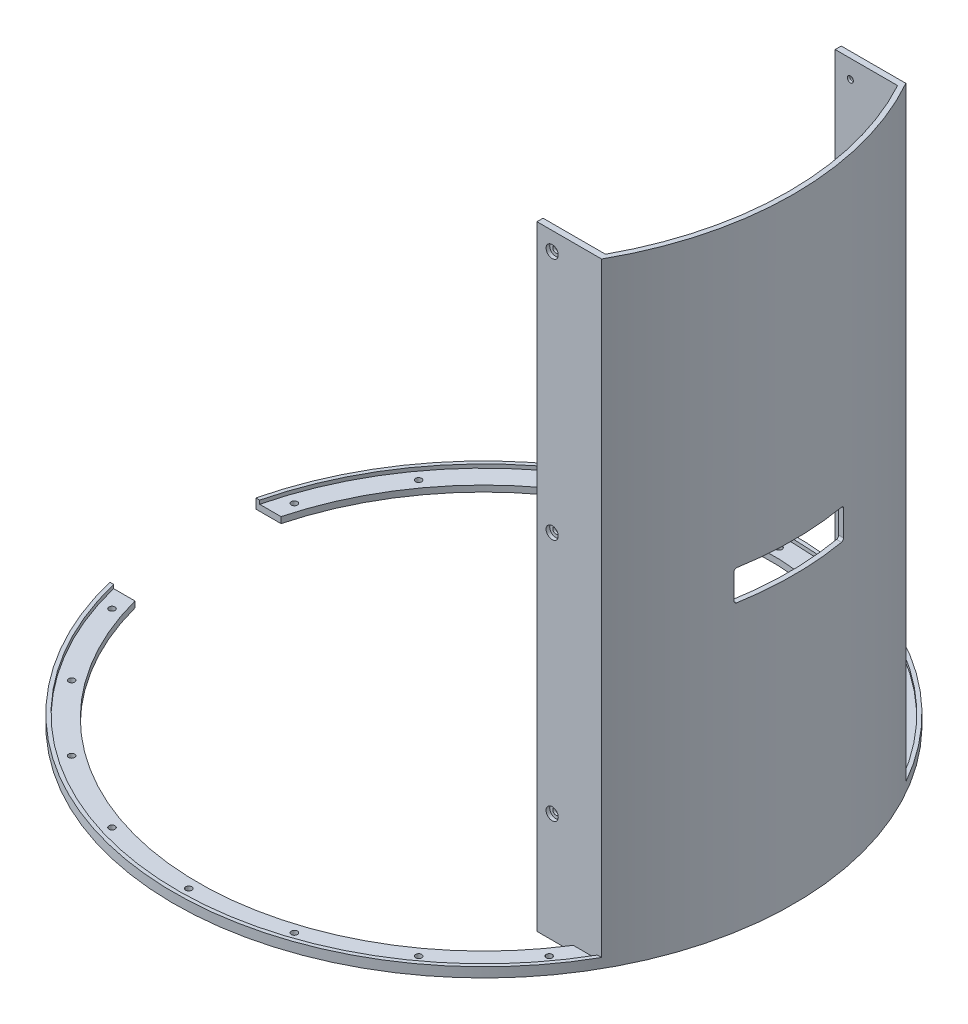
SolidWorks part; units mm, degrees
ref_plane "Front Plane" through (0, 0, 0) normal (0, 0, 1) x (1, 0, 0)
ref_plane "Top Plane" through (0, 0, 0) normal (0, 1, 0) x (1, 0, 0)
ref_plane "Right Plane" through (0, 0, 0) normal (1, 0, 0) x (0, 0, -1)
sketch "Sketch1" plane through (0, 0, 0) normal (0, 1, 0) x (1, 0, 0)
  circle A0 centre (0, 0) radius 254.5
  circle A1 centre (0, 0) radius 234.5
  dimension "D1" = 20
extrude "Boss-Extrude1" add sketch "Sketch1" along normal blind 5
sketch "Sketch2" plane through (0, 5, 0) normal (0, 1, 0) x (1, 0, 0)
  line L0 (254.5, 0) -> (234.5, 0)
  line L1 (221.6873, 125) -> (198.4068, 125)
  line L3 (168.5, 125) -> (165.5, 125) construction
  arc A0 (254.5, 0) -> (221.6873, 125) centre (0, 0) ccw
  circle A2 centre (0, 0) radius 254.5 construction
  circle A7 centre (0, 0) radius 234.5 construction
  arc A8 (198.4068, 125) -> (234.5, 0) centre (0, 0) cw
  dimension "D1" = 0
  dimension "D2" = 0
extrude "Boss-Extrude2" add sketch "Sketch2" along normal blind 500
mirror "Mirror1" about plane through (0, 505, 0) normal (0, 0, 1) of "Boss-Extrude2"
sketch "Sketch3" plane through (0, 5, 0) normal (0, 1, 0) x (1, 0, 0)
  line L1 (-254.5, 0) -> (-226.6942, 0)
  line L2 (-254.5, 0) -> (-254.5, 60)
  line L3 (-254.5, 60) -> (-226.6942, 60)
  line L4 (-226.6942, 0) -> (-226.6942, 60)
  arc A0 (221.6873, 125) -> (221.6873, -125) centre (0, 0) ccw construction
  arc A1 (198.4068, 125) -> (198.4068, -125) centre (0, 0) ccw construction
  dimension "D1" = 60
extrude "Cut-Extrude1" cut sketch "Sketch3" against normal blind 500
mirror "Mirror2" about plane through (0, 0, 0) normal (0, 0, 1) of "Cut-Extrude1"
sketch "Sketch4" plane through (0, 505, 0) normal (0, 1, 0) x (1, 0, 0)
  circle A0 centre (0, 0) radius 250.5
  arc A1 (221.6873, -125) -> (221.6873, 125) centre (0, 0) ccw construction
  dimension "D1" = 4
extrude "Cut-Extrude2" cut sketch "Sketch4" against normal blind 500
sketch "Sketch8" plane through (0, 5, 0) normal (0, 1, 0) x (1, 0, 0)
  line L0 (217.0835, 125) -> (168.5835, 125)
  line L1 (168.5835, 125) -> (168.5835, 120)
  line L2 (168.5835, 120) -> (220.0458, 120)
  line L3 (220.0458, 120) -> (220.0458, 125)
  line L4 (221.6873, 125) -> (217.0835, 125) construction
  line L5 (220.0458, 125) -> (217.0835, 125)
  dimension "D1" = 5
  dimension "D2" = 48.5
extrude "Boss-Extrude3" add sketch "Sketch8" along normal blind 500
mirror "Mirror3" about plane through (0, 0, 0) normal (0, 0, 1) of "Boss-Extrude3"
sketch "Sketch10" plane through (0, 0, 0) normal (0, -1, 0) x (1, 0, 0)
  line L0 (168.5835, 125) -> (168.5835, -125)
  line L1 (168.5835, 125) -> (208.5835, 125)
  line L2 (168.5835, -125) -> (208.5835, -125)
  arc A3 (208.5835, 125) -> (208.5835, -125) centre (0, 0) cw
  arc M3 (-226.6942, 60) -> (-226.6942, -60) centre (0, 0) cw
extrude "Boss-Extrude4" add sketch "Sketch10" against normal blind 5 contours L0 L2 L1 M3
sketch "Sketch11" plane through (0, 5, 0) normal (0, 1, 0) x (1, 0, 0)
  line L0 (168.5835, -120) -> (168.5835, 120) construction
  line L1 (168.5835, 93.5) -> (190, 93.5)
  line L2 (168.5835, 93.5) -> (168.5835, -96.5)
  line L3 (168.5835, -96.5) -> (190, -96.5)
  line L4 (190, 93.5) -> (190, -96.5)
  line L5 (188.5, -95) -> (188.5, -75) construction
  line L6 (168.5, -95) -> (188.5, -95) construction
  line L7 (188.5, 95) -> (168.5, 95) construction
  point P10 (178.5, -95)
  dimension "D1" = 1.5
  dimension "D2" = 1.5
  dimension "D3" = 1.5
extrude "Cut-Extrude3" cut sketch "Sketch11" against normal blind 10
sketch "Sketch12" plane through (0, 5, 0) normal (0, 1, 0) x (1, 0, 0)
  line L0 (-2.75, 0) -> (2.75, 0) construction
  line L1 (168.5835, 120) -> (185, 120)
  line L2 (168.5835, 120) -> (168.5835, 93.5)
  line L3 (168.5835, 93.5) -> (190, 93.5)
  line L4 (190, 115) -> (190, 93.5)
  line L5 (190, 93.5) -> (213, 93.5)
  line L6 (190, 93.5) -> (190, 75)
  line L7 (190, 75) -> (213, 75)
  line L8 (218, 88.5) -> (218, 80)
  line L9 (218, -88.5) -> (218, -80)
  line L10 (190, -75) -> (213, -75)
  line L11 (190, -93.5) -> (190, -75)
  line L12 (190, -93.5) -> (213, -93.5)
  line L13 (190, -115) -> (190, -93.5)
  line L14 (168.5835, -93.5) -> (190, -93.5)
  line L15 (168.5835, -120) -> (168.5835, -93.5)
  line L16 (168.5835, -120) -> (185, -120)
  arc A0 (213, -93.5) -> (218, -88.5) centre (213, -88.5) ccw
  arc A1 (218, -80) -> (213, -75) centre (213, -80) ccw
  arc A2 (190, -115) -> (185, -120) centre (185, -115) cw
  arc A3 (213, 75) -> (218, 80) centre (213, 80) ccw
  arc A4 (218, 88.5) -> (213, 93.5) centre (213, 88.5) ccw
  arc A5 (190, 115) -> (185, 120) centre (185, 115) ccw
  point P20 (218, -93.5)
  point P23 (218, -75)
  point P26 (190, -120)
  point P29 (218, 75)
  point P32 (218, 93.5)
  point P35 (190, 120)
  line M3 (190, 93.5) -> (190, -96.5)
  line M4 (190, -96.5) -> (168.5835, -96.5)
  line M5 (168.5835, -96.5) -> (168.5835, -120)
  line M6 (168.5835, -120) -> (219.8869, -120)
  dimension "D2" = 5
  dimension "D1" = 28
extrude "Cut-Extrude4" cut sketch "Sketch12" against normal blind 10 contours L8 L5 L7 M3 | L9 A1 L10 L12 A0 M3 | A2 L13 M4 M5 M6 | L4 A5 L1 L2 L3
fillet "Fillet1" radius 5 4 edges at (190, 2.5, 93.5) (190, 2.5, -93.5) (190, 2.5, -75) (190, 2.5, 75)
sketch "Sketch15" plane through (0, 5, 0) normal (0, 1, 0) x (1, 0, 0)
  circle A0 centre (242.5, 0) radius 2.5
  circle A1 centre (196.1866, -142.5379) radius 2.5
  circle A2 centre (74.9366, -230.6312) radius 2.5
  circle A3 centre (-74.9366, -230.6312) radius 2.5
  circle A4 centre (-196.1866, -142.5379) radius 2.5
  circle A5 centre (-242.5, 0) radius 2.5
  circle A6 centre (-196.1866, 142.5379) radius 2.5
  circle A7 centre (-74.9366, 230.6312) radius 2.5
  circle A8 centre (74.9366, 230.6312) radius 2.5
  circle A9 centre (196.1866, 142.5379) radius 2.5
  point P23 (0, 0)
  dimension "D1" = 242.5
  dimension "D2" = 10
extrude "Cut-Extrude5" cut sketch "Sketch15" against normal blind 10
sketch "Sketch16" plane through (0, 5, 0) normal (0, 1, 0) x (1, 0, 0)
  line L0 (-226.6942, 60) -> (-247.3262, 60) construction
  line L1 (221.6873, 125) -> (198.4068, 125) construction
  line L2 (-247.3262, 60) -> (-244.2381, 60)
  line L3 (221.6873, 125) -> (218.2367, 125)
  line L4 (-2.75, 0) -> (2.75, 0) construction
  line L5 (221.6873, -125) -> (218.2367, -125)
  line L6 (-247.3262, -60) -> (-244.2381, -60)
  arc A0 (221.6873, 125) -> (-247.3262, 60) centre (0, 0) ccw
  arc A1 (218.2367, 125) -> (-244.2381, 60) centre (0, 0) ccw
  arc A2 (218.2367, -125) -> (-244.2381, -60) centre (0, 0) cw
  arc A3 (221.6873, -125) -> (-247.3262, -60) centre (0, 0) cw
  dimension "D1" = 3
extrude "Boss-Extrude5" add sketch "Sketch16" along normal blind 3
sketch "Sketch18" plane through (0, 5, 0) normal (0, 1, 0) x (1, 0, 0)
  circle A0 centre (0, -242.5) radius 2.5
  circle A1 centre (-142.5379, -196.1866) radius 2.5
  circle A2 centre (-230.6312, -74.9366) radius 2.5
  circle A3 centre (-230.6312, 74.9366) radius 2.5
  circle A4 centre (-142.5379, 196.1866) radius 2.5
  circle A5 centre (0, 242.5) radius 2.5
  circle A6 centre (142.5379, 196.1866) radius 2.5
  circle A7 centre (230.6312, 74.9366) radius 2.5
  circle A8 centre (230.6312, -74.9366) radius 2.5
  circle A9 centre (142.5379, -196.1866) radius 2.5
  point P23 (0, 0)
  dimension "D1" = 242.5
  dimension "D2" = 10
extrude "Cut-Extrude6" cut sketch "Sketch18" against normal blind 5
sketch "Sketch19" plane through (0, 0, 0) normal (0, -1, 0) x (1, 0, 0)
  line L1 (193, 20) -> (207, 20)
  line L2 (190, 17) -> (190, -17)
  line L3 (193, -20) -> (207, -20)
  line L4 (210, 17) -> (210, -17)
  line L5 (193, -20) -> (190, -20)
  line L7 (190, -20) -> (190, -17)
  line L8 (193, 20) -> (190, 20)
  line L9 (190, 20) -> (190, 17)
  arc A1 (207, -20) -> (210, -17) centre (207, -17) ccw
  arc A2 (210, 17) -> (207, 20) centre (207, 17) ccw
  point P14 (190, 20)
extrude "Cut-Extrude7" cut sketch "Sketch19" against normal blind 7
fillet "Fillet2" radius 5 2 edges at (190, 2.5, 20) (190, 2.5, -20)
sketch "Sketch21" plane through (0, 5, 0) normal (0, 1, 0) x (1, 0, 0)
  line L0 (207, 20) -> (195, 20) construction
  line L1 (195, -20) -> (207, -20) construction
  line L2 (190, 25) -> (190, 70) construction
  line L3 (190, -70) -> (190, -25) construction
  circle A0 centre (200, 50) radius 2.5
  circle A1 centre (200, -50) radius 2.5
  dimension "D1" = 30
  dimension "D2" = 30
  dimension "D3" = 10
  dimension "D4" = 10
extrude "Cut-Extrude8" cut sketch "Sketch21" against normal blind 10
sketch "Sketch22" plane through (0, 0, 125) normal (0, 0, 1) x (1, 0, 0)
  line L0 (168.5835, 505) -> (168.5835, 0) construction
  line L1 (221.6873, 505) -> (168.5835, 505) construction
  circle A0 centre (181.0835, 490) radius 2.5
  circle A1 centre (181.0835, 290) radius 2.5
  circle A2 centre (181.0835, 90) radius 2.5
  dimension "D1" = 12.5
  dimension "D2" = 15
  dimension "D3" = 3
extrude "Cut-Extrude9" cut sketch "Sketch22" against normal blind 14
mirror "Mirror4" about plane through (0, 0, 0) normal (0, 0, 1) of "Cut-Extrude9"
sketch "Sketch23" plane through (0, 0, 125) normal (0, 0, 1) x (1, 0, 0)
  circle A0 centre (181.0835, 490) radius 5
  circle A1 centre (181.0835, 290) radius 5
  circle A2 centre (181.0835, 90) radius 5
  dimension "D1" = 3
extrude "Cut-Extrude10" cut sketch "Sketch23" against normal blind 3
mirror "Mirror5" about plane through (0, 0, 0) normal (0, 0, 1) of "Cut-Extrude10"
sketch "Sketch24" plane through (0, 0, 0) normal (0, 0, 1) x (1, 0, 0)
  line L0 (254.5, 0) -> (254.5, 505) construction
  line L1 (268.5989, 234) -> (240.4011, 234)
  line L2 (268.5989, 234) -> (268.5989, 259)
  line L3 (268.5989, 259) -> (240.4011, 259)
  line L4 (240.4011, 234) -> (240.4011, 259)
  line L5 (268.5989, 234) -> (240.4011, 259) construction
  line L6 (268.5989, 259) -> (240.4011, 234) construction
  line L7 (221.6873, 8) -> (-247.3262, 8) construction
  point P0 (254.5, 246.5)
  dimension "D1" = 226
  dimension "D2" = 25
extrude "Cut-Extrude11" cut sketch "Sketch24" against normal mid plane 90
fillet "Fillet3" radius 2 4 edges at (248.4575, 259, 45) (248.4575, 234, 45) (248.4575, 234, -45) (248.4575, 259, -45)
